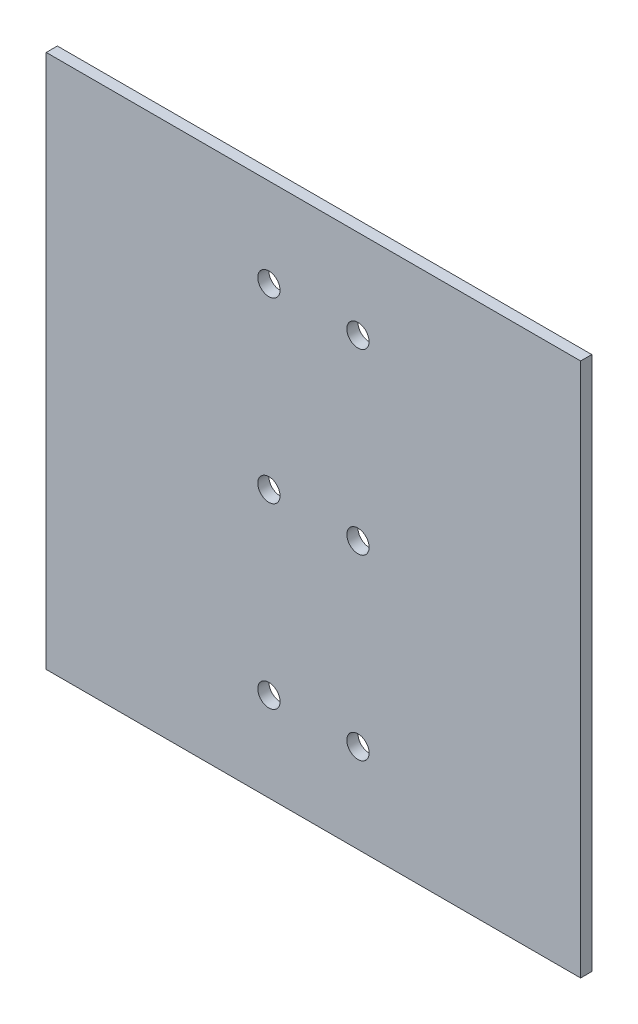
SolidWorks part; units mm, degrees
ref_plane "Front Plane" through (0, 0, 0) normal (0, 0, 1) x (1, 0, 0)
ref_plane "Top Plane" through (0, 0, 0) normal (0, 1, 0) x (1, 0, 0)
ref_plane "Right Plane" through (0, 0, 0) normal (1, 0, 0) x (0, 0, -1)
sketch "Sketch2" plane through (0, 0, 0) normal (0, 0, 1) x (1, 0, 0)
  line L0 (152.4, 304.8) -> (152.4, 0) construction
  line L1 (0, 0) -> (304.8, 0)
  line L2 (0, 0) -> (0, 304.8)
  line L3 (0, 304.8) -> (304.8, 304.8)
  line L4 (304.8, 0) -> (304.8, 304.8)
  line L5 (0, 0) -> (304.8, 304.8) construction
  line L6 (0, 304.8) -> (304.8, 0) construction
  circle A0 centre (177.8, 50.8) radius 6.35
  circle A1 centre (127, 50.8) radius 6.35
  circle A2 centre (127, 152.4) radius 6.35
  circle A3 centre (127, 254) radius 6.35
  circle A4 centre (177.8, 152.4) radius 6.35
  circle A5 centre (177.8, 254) radius 6.35
  point P4 (152.4, 152.4)
  dimension "D2" = 12.7
  dimension "D7" = 50.8
  dimension "D1" = 304.8
  dimension "D3" = 25.4
  dimension "D4" = 50.8
  dimension "D8" = 101.6
  dimension "D5" = 2
  dimension "D6" = 3
extrude "Boss-Extrude1" add sketch "Sketch2" along normal blind 6.35
